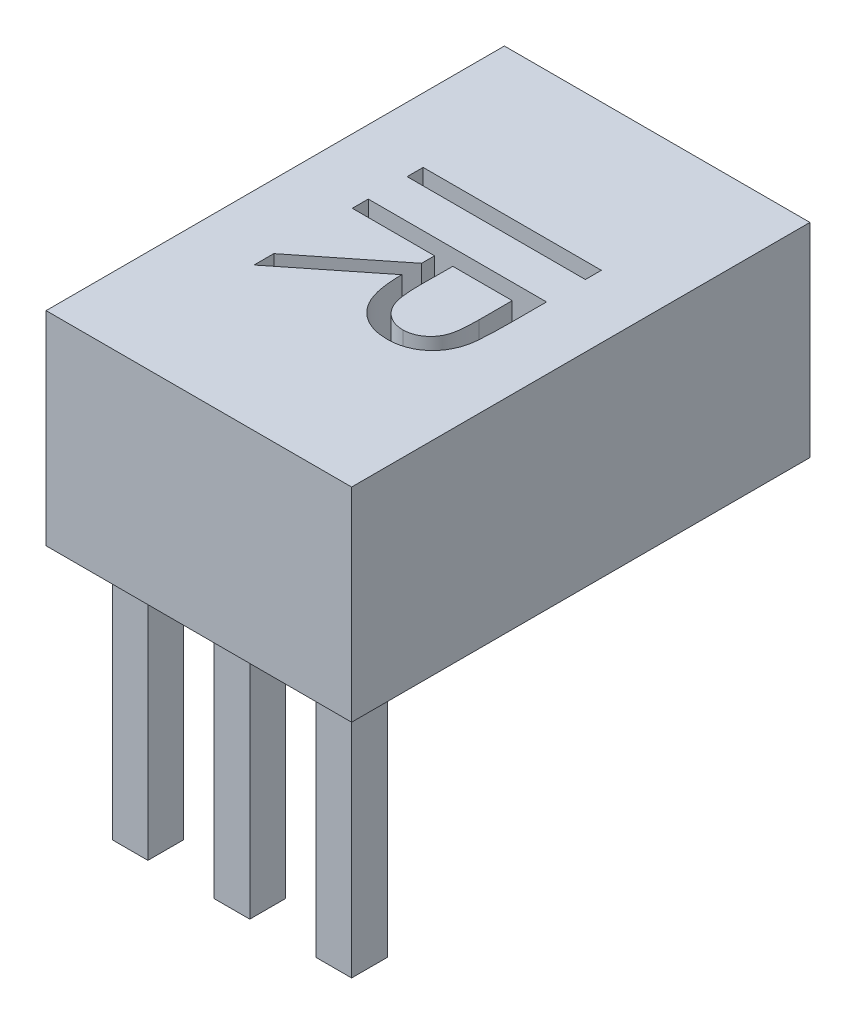
SolidWorks part; units mm, degrees
ref_plane "Front Plane" through (0, 0, 0) normal (0, 0, 1) x (1, 0, 0)
ref_plane "Top Plane" through (0, 0, 0) normal (0, 1, 0) x (1, 0, 0)
ref_plane "Right Plane" through (0, 0, 0) normal (1, 0, 0) x (0, 0, -1)
sketch "Sketch1" plane through (0, 0, 0) normal (0, 1, 0) x (1, 0, 0)
  line L1 (-3, 4.5) -> (3, 4.5)
  line L2 (-3, 4.5) -> (-3, -4.5)
  line L3 (-3, -4.5) -> (3, -4.5)
  line L4 (3, 4.5) -> (3, -4.5)
  line L5 (-3, 4.5) -> (3, -4.5) construction
  line L6 (-3, -4.5) -> (3, 4.5) construction
  point P0 (0, 0)
  dimension "D1" = 6
  dimension "D2" = 9
extrude "Boss-Extrude1" add sketch "Sketch1" along normal blind 4
sketch "Sketch2" plane through (0, 0, 0) normal (0, -1, 0) x (1, 0, 0)
  line L0 (0, -2.2) -> (0, 2.2) construction
  line L1 (-2.35, 3.85) -> (-1.65, 3.85)
  line L2 (-2.35, 3.85) -> (-2.35, 3.15)
  line L3 (-2.35, 3.15) -> (-1.65, 3.15)
  line L4 (-1.65, 3.85) -> (-1.65, 3.15)
  line L5 (-2.35, 3.85) -> (-1.65, 3.15) construction
  line L6 (-2.35, 3.15) -> (-1.65, 3.85) construction
  line L7 (-0.35, 3.85) -> (0.35, 3.85)
  line L8 (-0.35, 3.85) -> (-0.35, 3.15)
  line L9 (-0.35, 3.15) -> (0.35, 3.15)
  line L10 (0.35, 3.85) -> (0.35, 3.15)
  line L11 (-0.35, 3.85) -> (0.35, 3.15) construction
  line L12 (-0.35, 3.15) -> (0.35, 3.85) construction
  line L13 (1.65, 3.85) -> (2.35, 3.85)
  line L14 (1.65, 3.85) -> (1.65, 3.15)
  line L15 (1.65, 3.15) -> (2.35, 3.15)
  line L16 (2.35, 3.85) -> (2.35, 3.15)
  line L17 (1.65, 3.85) -> (2.35, 3.15) construction
  line L18 (1.65, 3.15) -> (2.35, 3.85) construction
  line L19 (-3, 4.5) -> (3, 4.5) construction
  point P0 (-2, 3.5)
  point P5 (0, 3.5)
  point P10 (2, 3.5)
  point P15 (0, 0)
  point P16 (0, 0)
  point P19 (0, 3.5064)
  point P20 (1.983, 3.4013)
  dimension "D1" = 0.7
  dimension "D2" = 2
  dimension "D3" = 2
  dimension "D4" = 1
extrude "Boss-Extrude2" add sketch "Sketch2" along normal blind 5
sketch "Sketch3" plane through (0, 4, 0) normal (0, 1, 0) x (1, 0, 0)
  line L0 (-1.7335, 3.2568) -> (-1.7335, -3.2568) construction
  text T0 "IR"
  point P3 (-1.7335, 0)
extrude "Cut-Extrude1" cut sketch "Sketch3" against normal blind 1
